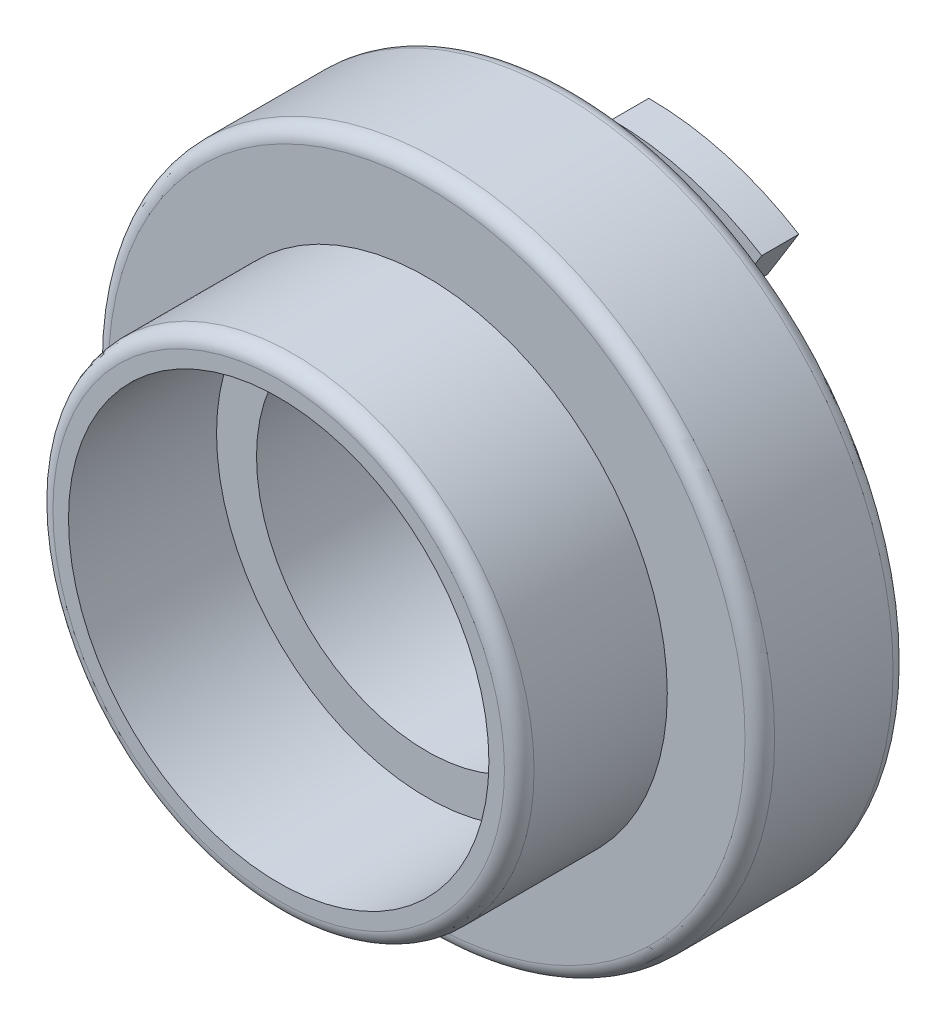
SolidWorks part; units mm, degrees
ref_plane "Front Plane" through (0, 0, 0) normal (0, 0, 1) x (1, 0, 0)
ref_plane "Top Plane" through (0, 0, 0) normal (0, 1, 0) x (1, 0, 0)
ref_plane "Right Plane" through (0, 0, 0) normal (1, 0, 0) x (0, 0, -1)
sketch "Sketch1" plane through (0, 0, 0) normal (0, 0, 1) x (1, 0, 0)
  circle A0 centre (0, 0) radius 41.275
  dimension "D1" = 82.55
extrude "Boss-Extrude1" add sketch "Sketch1" along normal blind 25.4
sketch "Sketch2" plane through (0, 0, 25.4) normal (0, 0, 1) x (1, 0, 0)
  circle A0 centre (0, 0) radius 36.068
  dimension "D1" = 72.136
extrude "Cut-Extrude1" cut sketch "Sketch2" against normal blind 25.4
sketch "Sketch3" plane through (0, 0, 0) normal (0, 0, -1) x (-1, 0, 0)
  circle A0 centre (0, 0) radius 57.15
  dimension "D1" = 114.3
extrude "Boss-Extrude2" add sketch "Sketch3" along normal blind 25.4
sketch "Sketch4" plane through (0, 0, -25.4) normal (0, 0, -1) x (-1, 0, 0)
  circle A0 centre (0, 0) radius 29.21
  dimension "D1" = 58.42
extrude "Cut-Extrude2" cut sketch "Sketch4" against normal through all
sketch "Sketch6" plane through (0, 0, -25.4) normal (0, 0, -1) x (-1, 0, 0)
  line L0 (0, 63.2231) -> (0, -63.2231) construction
  line L1 (-76.4882, 0) -> (76.4882, 0) construction
  line L2 (0, 0) -> (24.4547, -40.1251) construction
  line L3 (18.5063, -30.365) -> (24.4547, -40.1251)
  line L4 (0, 35.56) -> (0, 50.8)
  arc A0 (0, 50.8) -> (25.4, 43.9941) centre (0, 0) cw
  arc A1 (25.4, 43.9941) -> (27.139, 41.3524) centre (22.86, 40.4288) cw
  arc A2 (30.48, 35.7635) -> (24.4547, -40.1251) centre (0, 0) cw
  arc A3 (0, 35.56) -> (18.5063, -30.365) centre (0, 0) cw
  circle A4 centre (0, 0) radius 57.15 construction
  arc A5 (27.139, 41.3524) -> (30.48, 35.7635) centre (37.0703, 43.4962) ccw
  arc A6 (0, -46.99) -> (24.4547, -40.1251) centre (0, 0) ccw construction
  point P5 (0, 0)
  point P9 (0, 0)
  dimension "D1" = 50.8
  dimension "D2" = 22.86
  dimension "D3" = 46.99
  dimension "D4" = 25.4
  dimension "D5" = 30.48
  dimension "D6" = 25.4
  dimension "D7" = 15.24
extrude "Cut-Extrude4" cut sketch "Sketch6" against normal blind 22.86
ref_plane "Plane1" through (0, 0, -22.86) normal (0, 0, -1) x (-1, 0, 0)
sketch "Sketch8" plane through (0, 0, -22.86) normal (0, 0, -1) x (-1, 0, 0)
  line L0 (0, 0) -> (24.4547, -40.1251) construction
  line L1 (26.4375, -43.3785) -> (24.4547, -40.1251)
  arc A0 (26.4375, -43.3785) -> (25.4, 43.9941) centre (0, 0) ccw
  circle A1 centre (0, 0) radius 57.15 construction
  arc A2 (24.4547, -40.1251) -> (30.48, 35.7635) centre (0, 0) ccw
  arc A3 (30.48, 35.7635) -> (27.139, 41.3524) centre (37.0703, 43.4962) cw
  arc A5 (25.4, 43.9941) -> (27.139, 41.3524) centre (22.86, 40.4288) cw
extrude "Cut-Extrude5" cut sketch "Sketch8" against normal blind 20.32
sketch "Sketch9" plane through (0, 0, -25.4) normal (0, 0, -1) x (-1, 0, 0)
  line L0 (0, 65.6273) -> (0, -65.6273) construction
  line L1 (0, 44.45) -> (0, 38.608)
  line L2 (0, 0) -> (-23.4488, 37.7618) construction
  line L3 (-20.367, 32.7988) -> (-23.4488, 37.7618)
  arc A0 (0, 44.45) -> (-23.4488, 37.7618) centre (0, 0) ccw
  circle A2 centre (0, 0) radius 57.15 construction
  arc A3 (0, 38.608) -> (-20.367, 32.7988) centre (0, 0) ccw
  point P6 (0, 0)
  dimension "D1" = 3.048
  dimension "D2" = 6.35
  dimension "D3" = 24.384
extrude "Boss-Extrude3" add sketch "Sketch9" along normal blind 6.35
sketch "Sketch10" plane through (0, 0, -31.75) normal (0, 0, -1) x (-1, 0, 0)
  line L0 (0, 0) -> (-23.4488, 37.7618) construction
  line L1 (-20.367, 32.7988) -> (-25.7267, 41.4301)
  line L2 (0, 0) -> (0, 44.45) construction
  line L3 (0, 48.768) -> (0, 38.608)
  arc A0 (-20.367, 32.7988) -> (0, 38.608) centre (0, 0) cw
  arc A3 (0, 38.608) -> (-20.367, 32.7988) centre (0, 0) ccw construction
  arc A4 (-25.7267, 41.4301) -> (0, 48.768) centre (0, 0) cw
  arc A5 (0, 44.45) -> (-23.4488, 37.7618) centre (0, 0) ccw construction
  dimension "D1" = 10.16
  dimension "D2" = 10.16
extrude "Boss-Extrude4" add sketch "Sketch10" along normal blind 6.35
sketch "Sketch11" plane through (0, 0, -25.4) normal (0, 0, -1) x (-1, 0, 0)
  line L0 (0, 0) -> (0, -62.7191) construction
  line L1 (18.5063, -30.365) -> (24.4547, -40.1251) construction
  line L2 (0, -46.228) -> (0, -38.608)
  line L3 (24.0582, -39.4745) -> (20.0925, -32.9677)
  arc A0 (20.0925, -32.9677) -> (0, -38.608) centre (0, 0) cw
  arc A1 (0, 38.608) -> (-20.367, 32.7988) centre (0, 0) ccw construction
  arc A2 (0, -46.228) -> (24.0582, -39.4745) centre (0, 0) ccw
  dimension "D1" = 38.608
  dimension "D2" = 46.228
extrude "Boss-Extrude5" add sketch "Sketch11" along normal blind 6.35
sketch "Sketch12" plane through (0, 0, -31.75) normal (0, 0, -1) x (-1, 0, 0)
  line L2 (0, -38.608) -> (0, -48.768)
  line L3 (0, 0) -> (24.2564, -39.7998) construction
  line L4 (24.0582, -39.4745) -> (24.4547, -40.1251) construction
  line L5 (20.0925, -32.9677) -> (25.38, -41.6434)
  arc A0 (0, -38.608) -> (20.0925, -32.9677) centre (0, 0) ccw
  arc A1 (0, -38.608) -> (20.0925, -32.9677) centre (0, 0) ccw construction
  arc A2 (0, -48.768) -> (25.38, -41.6434) centre (0, 0) ccw
  arc A3 (0, -46.228) -> (24.0582, -39.4745) centre (0, 0) ccw construction
  dimension "D1" = 10.16
extrude "Boss-Extrude6" add sketch "Sketch12" along normal blind 6.35
sketch "Sketch13" plane through (0, 0, -25.4) normal (0, 0, -1) x (-1, 0, 0)
  line L0 (0, 0) -> (-20.367, 32.7988) construction
  line L1 (0, -35.56) -> (0, -50.8)
  line L2 (-24.7888, 39.9196) -> (-18.7591, 30.2095)
  arc A0 (0, -35.56) -> (-18.7591, 30.2095) centre (0, 0) cw
  arc A1 (18.5063, -30.365) -> (0, 35.56) centre (0, 0) ccw construction
  arc A2 (18.5063, -30.365) -> (0, 35.56) centre (0, 0) ccw construction
  arc A3 (0, -50.8) -> (-25.4, -43.9941) centre (0, 0) cw
  arc A4 (-25.4, -43.9941) -> (-27.915, -39.091) centre (-22.86, -39.5947) cw
  arc A5 (-27.915, -39.091) -> (-30.48, -35.7635) centre (-37.0703, -43.4962) ccw
  circle A6 centre (0, 0) radius 57.15 construction
  arc A7 (-30.48, -35.7635) -> (-24.7888, 39.9196) centre (0, 0) cw
  dimension "D3" = 46.99
  dimension "D1" = 15.24
  dimension "D2" = 25.4
  dimension "D4" = 22.86
  dimension "D5" = 30.48
extrude "Cut-Extrude6" cut sketch "Sketch13" against normal blind 22.86
sketch "Sketch14" plane through (0, 0, -22.86) normal (0, 0, -1) x (-1, 0, 0)
  line L0 (0, 0) -> (-25.7267, 41.4301) construction
  line L1 (-26.7987, 43.1564) -> (-24.7888, 39.9196)
  arc A0 (-25.4, -43.9941) -> (-26.7987, 43.1564) centre (0, 0) cw
  arc A1 (-25.4, -43.9941) -> (0, -50.8) centre (0, 0) ccw construction
  arc A2 (-18.7591, 30.2095) -> (0, -35.56) centre (0, 0) ccw construction
  arc A3 (-24.7888, 39.9196) -> (-30.48, -35.7635) centre (0, 0) ccw
  arc A4 (-24.7888, 39.9196) -> (-30.48, -35.7635) centre (0, 0) ccw construction
  arc A5 (-30.48, -35.7635) -> (-27.915, -39.091) centre (-37.0703, -43.4962) cw
  arc A6 (-27.915, -39.091) -> (-25.4, -43.9941) centre (-22.86, -39.5947) ccw
  arc A7 (-27.915, -39.091) -> (-25.4, -43.9941) centre (-22.86, -39.5947) ccw construction
  point P0 (-25.4, -43.9941)
  point P27 (-24.3232, -40.3452)
  point P32 (-24.7888, -43.9941)
extrude "Cut-Extrude7" cut sketch "Sketch14" against normal blind 20.32
sketch "Sketch15" plane through (0, 0, -25.4) normal (0, 0, -1) x (-1, 0, 0)
  circle A0 centre (0, 0) radius 30.48
  circle A1 centre (0, 0) radius 34.29
  dimension "D1" = 68.58
  dimension "D2" = 60.96
extrude "Cut-Extrude8" cut sketch "Sketch15" against normal blind 12.7
fillet "Fillet1" radius 2.54 3 edges at (41.275, 0, 25.4) (-57.15, 0, 0) (-57.15, 0, -25.4)
